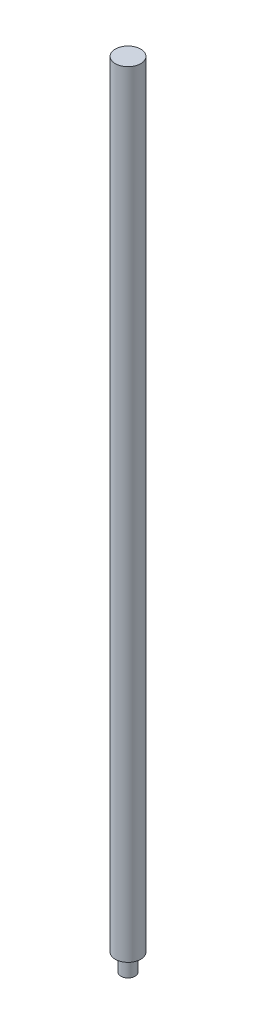
SolidWorks part; units mm, degrees
ref_plane "前视基准面" through (0, 0, 0) normal (0, 0, 1) x (1, 0, 0)
ref_plane "上视基准面" through (0, 0, 0) normal (0, 1, 0) x (1, 0, 0)
ref_plane "右视基准面" through (0, 0, 0) normal (1, 0, 0) x (0, 0, -1)
other "Configuration Table"
sketch "草图1" plane through (0, 0, 0) normal (0, 1, 0) x (1, 0, 0)
  circle A0 centre (0, 0) radius 8
  dimension "D1" = 16
extrude "凸台-拉伸1" add sketch "草图1" along normal blind 500
cosmetic thread "装饰螺纹线1" parameters "D2"=15
sketch "草图2" plane through (0, 0, 0) normal (0, -1, 0) x (1, 0, 0)
  circle A0 centre (0, 0) radius 4.5
  dimension "D1" = 9
extrude "切除-拉伸1" cut sketch "草图2" against normal blind 11 flip side to cut
